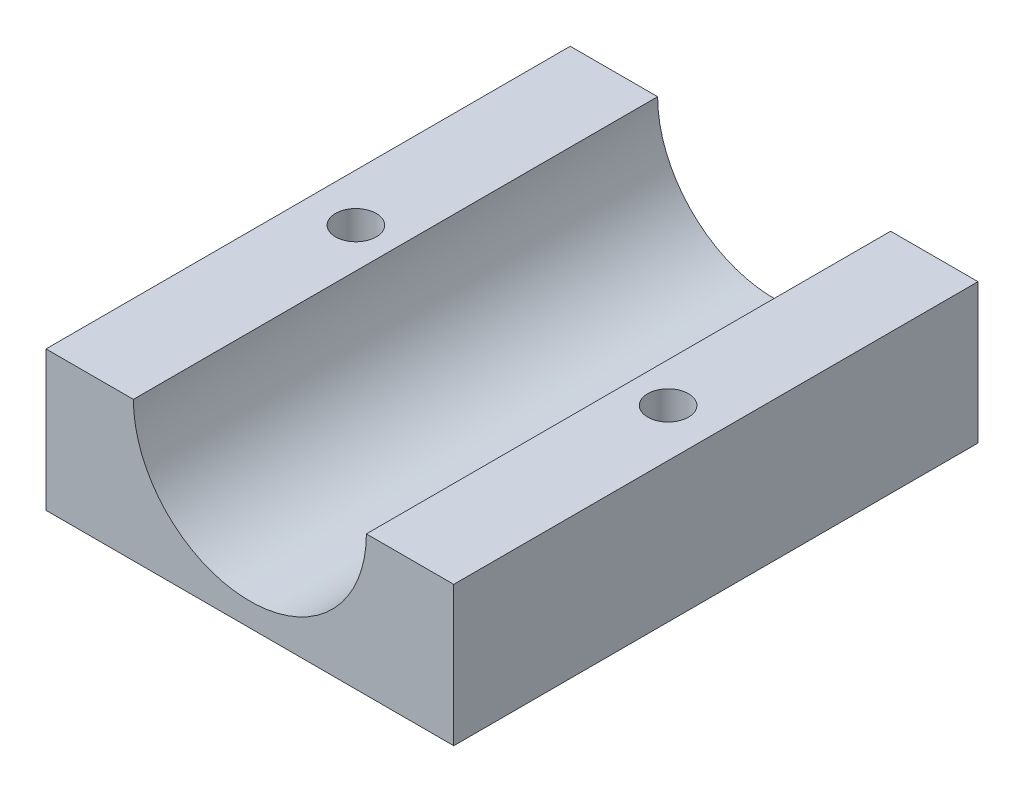
SolidWorks part; units mm, degrees
ref_plane "Front Plane" through (0, 0, 0) normal (0, 0, 1) x (1, 0, 0)
ref_plane "Top Plane" through (0, 0, 0) normal (0, 1, 0) x (1, 0, 0)
ref_plane "Right Plane" through (0, 0, 0) normal (1, 0, 0) x (0, 0, -1)
sketch "Sketch1" plane through (0, 0, 0) normal (0, 1, 0) x (1, 0, 0)
  line L1 (0, 0) -> (35, 0)
  line L2 (0, 0) -> (0, 45)
  line L3 (0, 45) -> (35, 45)
  line L4 (35, 0) -> (35, 45)
  dimension "D1" = 45
  dimension "D2" = 35
extrude "Boss-Extrude1" add sketch "Sketch1" along normal blind 12
sketch "Sketch2" plane through (0, 0, 0) normal (0, 0, 1) x (1, 0, 0)
  line L0 (0, 12) -> (35, 12) construction
  circle A0 centre (17.5, 12) radius 10
extrude "Cut-Extrude1" cut sketch "Sketch2" against normal through all
sketch "Sketch3" plane through (0, 12, 0) normal (0, 1, 0) x (1, 0, 0)
  circle A0 centre (30.9, 22.5) radius 1.75
  circle A1 centre (4.1, 22.5) radius 1.75
extrude "Cut-Extrude2" cut sketch "Sketch3" against normal blind 25
